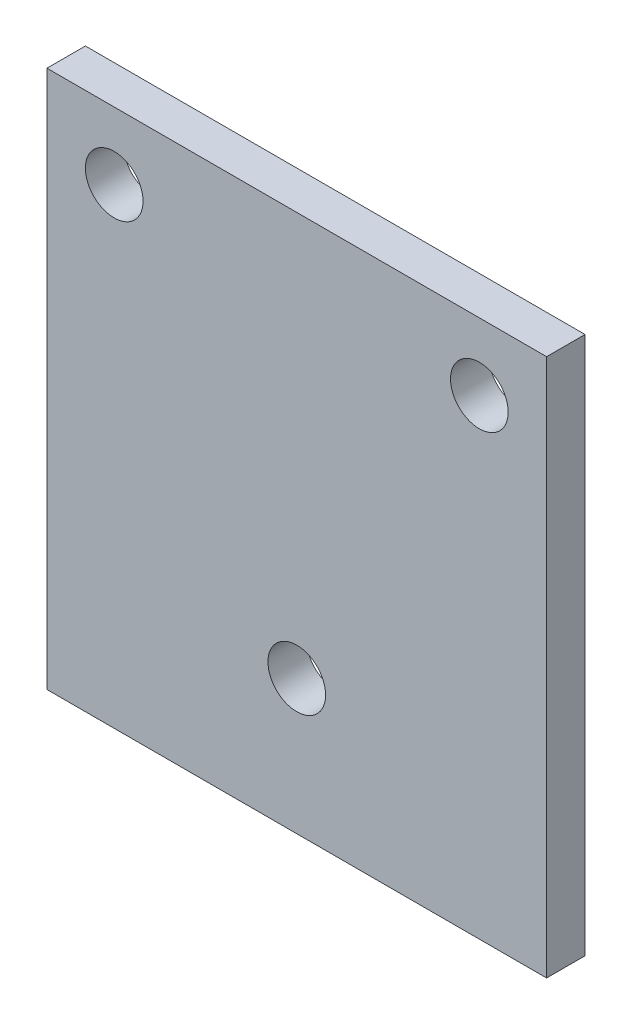
SolidWorks part; units mm, degrees
ref_plane "Alzado" through (0, 0, 0) normal (0, 0, 1) x (1, 0, 0)
ref_plane "Planta" through (0, 0, 0) normal (0, 1, 0) x (1, 0, 0)
ref_plane "Vista lateral" through (0, 0, 0) normal (1, 0, 0) x (0, 0, -1)
sketch "Croquis1" plane through (0, 0, 0) normal (0, 0, 1) x (1, 0, 0)
  line L0 (-27.8873, 15.5366) -> (-27.8873, -12.4634) construction
  line L1 (-40.8873, 15.5366) -> (-14.8873, 15.5366)
  line L2 (-40.8873, 15.5366) -> (-40.8873, -12.4634)
  line L3 (-40.8873, -12.4634) -> (-14.8873, -12.4634)
  line L4 (-14.8873, 15.5366) -> (-14.8873, -12.4634)
  circle A0 centre (-37.3873, 12.0366) radius 1.5
  circle A1 centre (-18.3873, 12.0366) radius 1.5
  circle A2 centre (-27.8873, -5.4634) radius 1.5
  point P6 (-27.8873, 15.5366)
  dimension "D3" = 9.5
  dimension "D5" = 21
  dimension "D1" = 26
  dimension "D2" = 28
  dimension "D4" = 3.5
extrude "Saliente-Extruir1" add sketch "Croquis1" along normal blind 2
